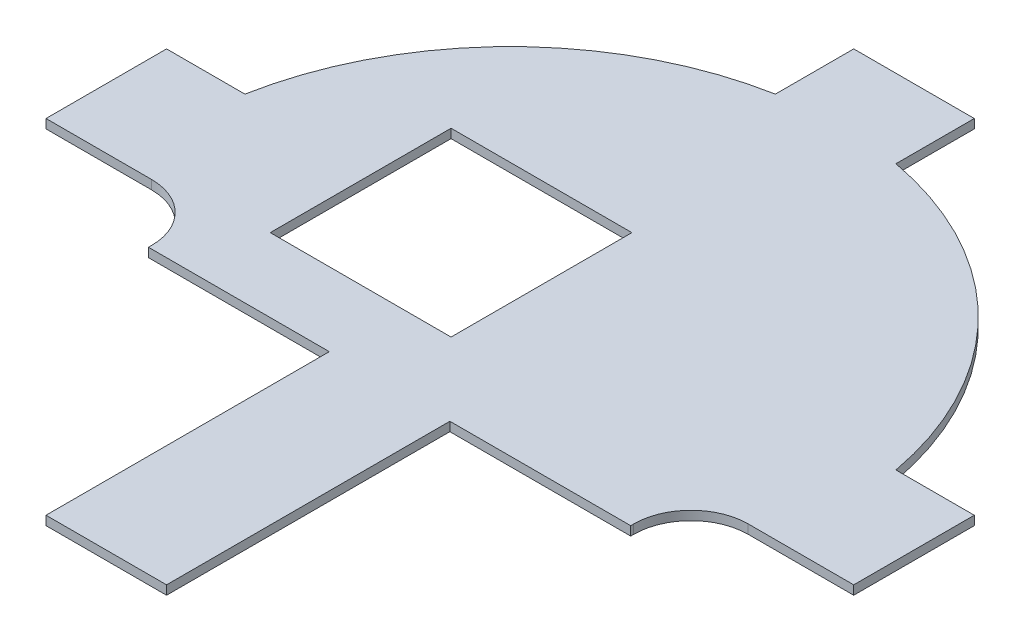
SolidWorks part; units mm, degrees
ref_plane "Alzado" through (0, 0, 0) normal (0, 0, 1) x (1, 0, 0)
ref_plane "Planta" through (0, 0, 0) normal (0, 1, 0) x (1, 0, 0)
ref_plane "Vista lateral" through (0, 0, 0) normal (1, 0, 0) x (0, 0, -1)
sketch "Croquis1" plane through (0, 0, 0) normal (0, 1, 0) x (1, 0, 0)
  line L0 (-40.3545, -55.2134) -> (-40.3545, -54.7134)
  line L1 (-67.3545, 31.7866) -> (66.6455, 31.7866)
  line L2 (-67.3545, 31.7866) -> (-67.3545, -102.2134)
  line L3 (-67.3545, -102.2134) -> (66.6455, -102.2134)
  line L4 (66.6455, 31.7866) -> (66.6455, -102.2134)
  line L5 (39.6455, -55.2134) -> (39.6455, -54.7134)
  line L6 (-10.3545, 31.7866) -> (-10.3545, -102.2134)
  line L7 (-49.8545, -45.2134) -> (-67.3545, -45.2134)
  line L8 (9.6455, 31.7866) -> (9.6455, -102.2134)
  line L10 (66.6455, -25.2134) -> (53.6455, -25.2134)
  line L11 (-10.3545, -55.2134) -> (-40.3545, -55.2134)
  line L12 (9.6455, -55.2134) -> (39.6455, -55.2134)
  line L13 (49.1455, -45.2134) -> (66.6455, -45.2134)
  line L14 (-67.3545, -25.2134) -> (-54.3545, -25.2134)
  line L15 (66.6455, -25.2134) -> (53.6455, -25.2134)
  line L16 (-67.3545, -25.2134) -> (-54.3545, -25.2134)
  arc A0 (-40.3545, -54.7134) -> (-49.8545, -45.2134) centre (-49.8545, -54.7134) ccw
  arc A1 (39.6455, -54.7134) -> (49.1455, -45.2134) centre (49.1455, -54.7134) cw
  arc A3 (-54.3545, -25.2134) -> (53.6455, -25.2134) centre (-0.3545, -35.2134) cw
  dimension "D4" = 9.5
  dimension "D1" = 134
  dimension "D2" = 134
  dimension "D3" = 31.7866
  dimension "D6" = 47
  dimension "D7" = 30
  dimension "D8" = 30
  dimension "D9" = 20
  dimension "D5" = 57
  dimension "D10" = 57
  dimension "D11" = 57
  dimension "D12" = 57
  dimension "D13" = 20
  dimension "D14" = 57
  dimension "D15" = 13
  dimension "D16" = 57
  dimension "D17" = 13
extrude "Saliente-Extruir1" add sketch "Croquis1" along normal blind 1.5 contours A3 L6 L3 L8 | A3 L8 L12 L5 A1 L13 L4 L10 | A3 L14 L2 L7 A0 L0 L11 L6 | L6 A3 L8 L1
sketch "Croquis2" plane through (0, 1.5, 0) normal (0, 1, 0) x (1, 0, 0)
  line L0 (-67.3545, -25.2134) -> (-67.3545, -45.2134) construction
  line L3 (-32.3545, -43.0134) -> (-2.3545, -43.0134)
  line L4 (-32.3545, -43.0134) -> (-32.3545, -13.0134)
  line L5 (-32.3545, -13.0134) -> (-2.3545, -13.0134)
  line L6 (-2.3545, -43.0134) -> (-2.3545, -13.0134)
  dimension "D1" = 30
  dimension "D2" = 30
  dimension "D3" = 35
extrude "Cortar-Extruir1" cut sketch "Croquis2" against normal through all
